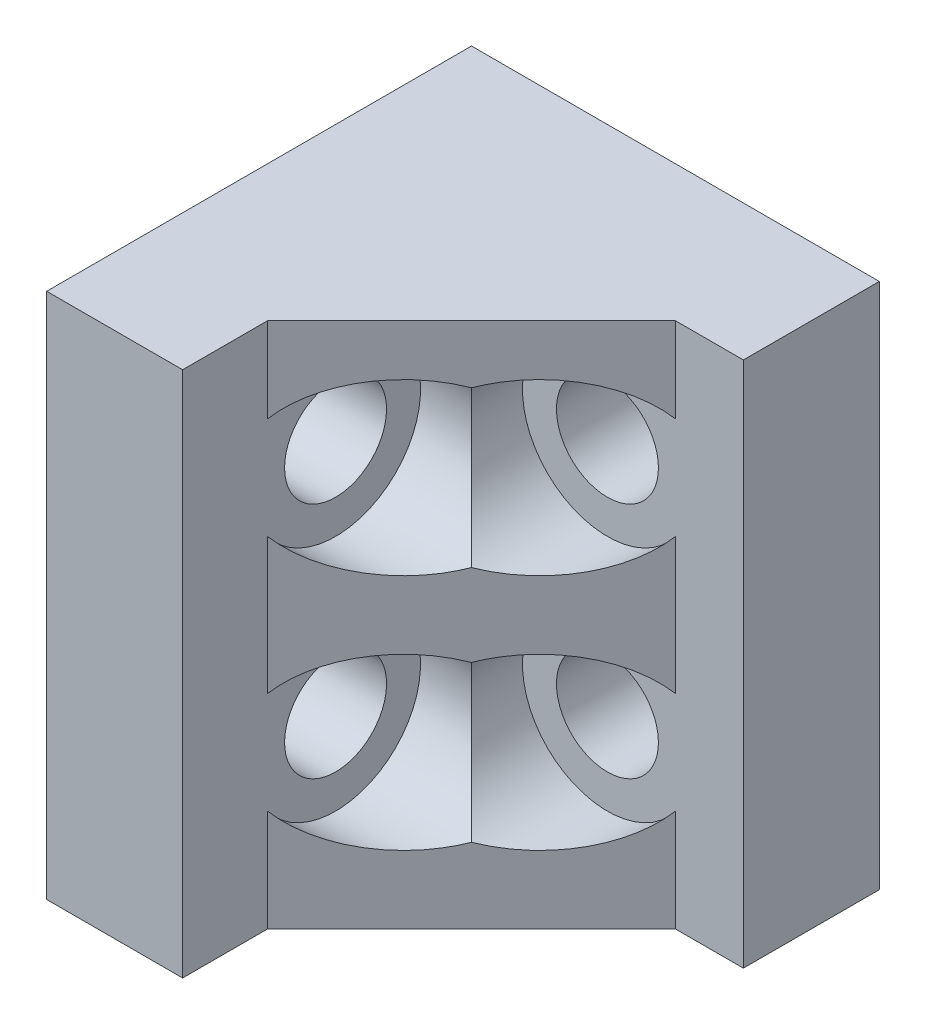
SolidWorks part; units mm, degrees
ref_plane "Front Plane" through (0, 0, 0) normal (0, 0, 1) x (1, 0, 0)
ref_plane "Top Plane" through (0, 0, 0) normal (0, 1, 0) x (1, 0, 0)
ref_plane "Right Plane" through (0, 0, 0) normal (1, 0, 0) x (0, 0, -1)
sketch "Sketch1" plane through (0, 0, 0) normal (0, 0, 1) x (1, 0, 0)
  line L1 (47.7804, 35.847) -> (-22.2196, 35.847) construction
  line L2 (1.7804, 35.847) -> (13.7804, 35.847)
  line L3 (1.7804, 35.847) -> (1.7804, 20.347)
  line L4 (1.7804, 20.347) -> (13.7804, 20.347)
  line L5 (13.7804, 35.847) -> (13.7804, 20.347)
  line L6 (1.7804, -14.153) -> (1.7804, 35.847) construction
  line L8 (17.7804, 20.347) -> (7.7804, 20.347) construction
  dimension "D1" = 0
  dimension "D2" = 0
  dimension "D3" = 12
  dimension "D4" = 0
extrude "Boss-Extrude1" add sketch "Sketch1" along normal blind 4
sketch "Sketch2" plane through (0, 0, 4) normal (0, 0, 1) x (1, 0, 0)
  line L0 (13.7804, 35.847) -> (1.7804, 35.847) construction
  line L1 (1.7804, 20.347) -> (5.7804, 20.347)
  line L2 (1.7804, 20.347) -> (1.7804, 35.847)
  line L3 (1.7804, 35.847) -> (5.7804, 35.847)
  line L4 (5.7804, 20.347) -> (5.7804, 35.847)
  dimension "D1" = 4
extrude "Boss-Extrude2" add sketch "Sketch2" along normal up to vertex (8.5 mm away)
sketch "Sketch3" plane through (5.7804, 0, 0) normal (1, 0, 0) x (0, 0, -1)
  line L0 (0, 20.347) -> (0, 35.847) construction
  line L1 (-12.5, 35.847) -> (-4, 35.847) construction
  line L3 (-4, 20.347) -> (-4, 35.847) construction
  circle A0 centre (-8, 24.847) radius 1.5
  circle A1 centre (-8, 31.847) radius 1.5
  point P8 (-8.25, 35.847)
  dimension "D1" = 3
  dimension "D2" = 3
  dimension "D3" = 8
  dimension "D4" = 0
  dimension "D5" = 4
  dimension "D6" = 7
extrude "Cut-Extrude1" cut sketch "Sketch3" against normal blind 5
sketch "Sketch4" plane through (0, 0, 4) normal (0, 0, 1) x (1, 0, 0)
  line L1 (13.7804, 35.847) -> (5.7804, 35.847) construction
  line L2 (13.7804, 20.347) -> (13.7804, 35.847) construction
  circle A0 centre (9.7804, 24.847) radius 1.5
  circle A1 centre (9.7804, 31.847) radius 1.5
  dimension "D1" = 3
  dimension "D2" = 3
  dimension "D4" = 4
  dimension "D5" = 0
  dimension "D6" = 4
  dimension "D3" = 7
extrude "Cut-Extrude2" cut sketch "Sketch4" against normal blind 5
sketch "Sketch5" plane through (0, 35.847, 0) normal (0, 1, 0) x (1, 0, 0)
  line L0 (5.7804, -4) -> (5.7804, -10)
  line L1 (5.7804, -12.5) -> (5.7804, -4) construction
  line L2 (5.7804, -10) -> (11.7804, -4)
  line L3 (13.7804, -4) -> (5.7804, -4) construction
  line L4 (11.7804, -4) -> (5.7804, -4)
  dimension "D1" = 6
  dimension "D2" = 6
extrude "Boss-Extrude3" add sketch "Sketch5" against normal up to vertex (15.5 mm away)
sketch "Sketch6" plane through (13.7804, 0, 0) normal (1, 0, 0) x (0, 0, -1)
  line L3 (0, 35.847) -> (0, 20.347) construction
  line L5 (-12.5, 35.847) -> (0, 35.847) construction
  circle A0 centre (-8, 31.847) radius 2.5
  circle A1 centre (-8, 24.847) radius 2.5
  point P2 (0, 0)
  dimension "D1" = 5
  dimension "D2" = 5
  dimension "D3" = 8
  dimension "D4" = 7
  dimension "D5" = 4
  dimension "D6" = 0
extrude "Cut-Extrude3" cut sketch "Sketch6" against normal blind 8
sketch "Sketch7" plane through (0, 0, 12.5) normal (0, 0, 1) x (1, 0, 0)
  line L3 (13.7804, 20.347) -> (13.7804, 35.847) construction
  circle A0 centre (9.7804, 31.847) radius 2.5
  circle A1 centre (9.7804, 24.847) radius 2.5
  arc A2 (5.7804, 23.347) -> (5.7804, 26.347) centre (7.7804, 24.847) ccw construction
  arc A3 (5.7804, 30.347) -> (5.7804, 33.347) centre (7.7804, 31.847) ccw construction
  dimension "D1" = 5
  dimension "D2" = 0
  dimension "D3" = 0
  dimension "D4" = 0
  dimension "D5" = 4
extrude "Cut-Extrude4" cut sketch "Sketch7" against normal up to vertex (8.5 mm away)
